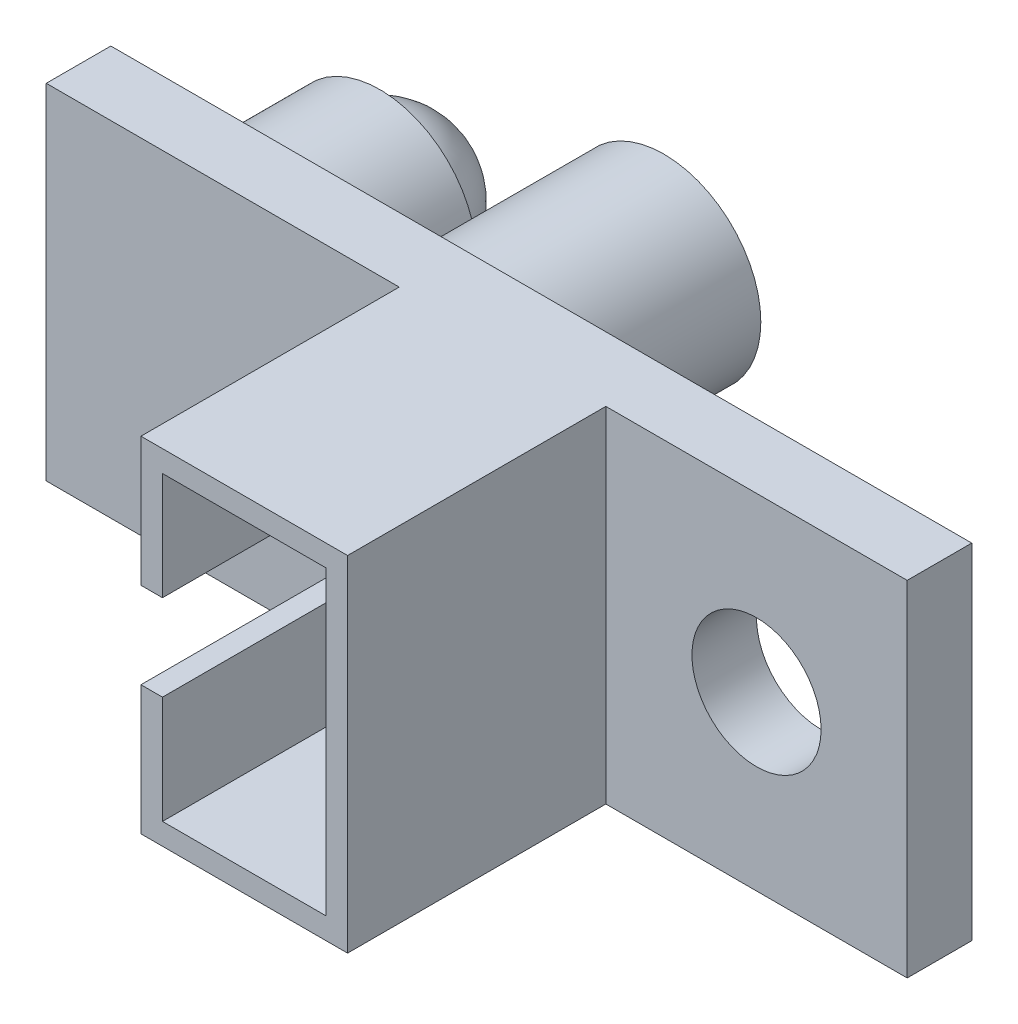
SolidWorks part; units mm, degrees
ref_plane "前视基准面" through (0, 0, 0) normal (0, 0, 1) x (1, 0, 0)
ref_plane "上视基准面" through (0, 0, 0) normal (0, 1, 0) x (1, 0, 0)
ref_plane "右视基准面" through (0, 0, 0) normal (1, 0, 0) x (0, 0, -1)
sketch "草图1" plane through (0, 0, 0) normal (0, 0, 1) x (1, 0, 0)
  line L1 (-10, 4) -> (10, 4)
  line L2 (-10, 4) -> (-10, -4)
  line L3 (-10, -4) -> (10, -4)
  line L4 (10, 4) -> (10, -4)
  line L5 (-10, 4) -> (10, -4) construction
  line L6 (-10, -4) -> (10, 4) construction
  point P0 (0, 0)
  dimension "D1" = 8
  dimension "D2" = 20
extrude "凸台-拉伸1" add sketch "草图1" along normal blind 1.5
sketch "草图2" plane through (0, 0, 1.5) normal (0, 0, 1) x (1, 0, 0)
  line L0 (10, -4) -> (10, 4) construction
  circle A0 centre (6.5, 0) radius 1.5
  dimension "D1" = 3
  dimension "D2" = 3.5
extrude "切除-拉伸1" cut sketch "草图2" against normal blind 1.5
sketch "草图3" plane through (0, 0, 1.5) normal (0, 0, 1) x (1, 0, 0)
  line L0 (10, 4) -> (-10, 4) construction
  line L1 (-1.8, 4) -> (3, 4)
  line L2 (-1.8, 4) -> (-1.8, -4)
  line L3 (-1.8, -4) -> (3, -4)
  line L4 (3, 4) -> (3, -4)
  line L5 (-10, -4) -> (10, -4) construction
  line L6 (10, -4) -> (10, 4) construction
  line L7 (-1.3, 3.5) -> (2.5, 3.5)
  line L8 (2.5, 3.5) -> (2.5, -3.5)
  line L9 (-1.3, -3.5) -> (2.5, -3.5)
  line L10 (-1.3, 3.5) -> (-1.3, -3.5)
  dimension "D1" = 7
  dimension "D2" = 4.8
  dimension "D3" = 0.5
extrude "凸台-拉伸2" add sketch "草图3" along normal blind 6
sketch "草图4" plane through (-1.8, 0, 0) normal (-1, 0, 0) x (0, 0, 1)
  line L0 (7.5, 4) -> (7.5, -4) construction
  line L1 (3, 1) -> (7.5, 1)
  line L2 (3, 1) -> (3, -1)
  line L3 (3, -1) -> (7.5, -1)
  line L4 (7.5, 1) -> (7.5, -1)
  line L5 (3, 1) -> (7.5, -1) construction
  line L6 (3, -1) -> (7.5, 1) construction
  point P0 (5.25, 0)
  dimension "D1" = 4.5
  dimension "D2" = 2
extrude "切除-拉伸4" cut sketch "草图4" against normal blind 1
sketch "草图5" plane through (0, 0, 0) normal (0, 0, -1) x (-1, 0, 0)
  line L0 (10, 4) -> (10, -4) construction
  line L1 (5.5, 0) -> (5.5, 1.5149) construction
  circle A0 centre (7.75, 0) radius 2.25
  circle A1 centre (7.75, 0) radius 1.75
  dimension "D1" = 4.5
  dimension "D2" = 0.5
extrude "凸台-拉伸3" add sketch "草图5" along normal blind 4
sketch "草图6" plane through (0, 0, -4) normal (0, 0, -1) x (-1, 0, 0)
  line L0 (7.75, 1.75) -> (7.75, -1.75)
  circle A0 centre (7.75, 0) radius 1.75 construction
  arc A1 (7.75, -1.75) -> (7.75, 1.75) centre (7.75, 0) ccw
revolve "旋转1" add sketch "草图6" angle 360 about L0
sketch "草图8" plane through (0, 0, 0) normal (0, 0, -1) x (-1, 0, 0)
  circle A0 centre (3.15, 0) radius 2.25
  circle A2 centre (3.15, 0) radius 1.75
  circle A3 centre (7.75, 0) radius 2.25 construction
  dimension "D1" = 4.5
  dimension "D2" = 3.5
  dimension "D3" = 4.6
extrude "凸台-拉伸13" add sketch "草图8" along normal blind 4
sketch "草图9" plane through (0, 0, -4) normal (0, 0, -1) x (-1, 0, 0)
  line L0 (3.15, 1.75) -> (3.15, -1.75)
  circle A0 centre (3.15, 0) radius 1.75 construction
  arc A1 (3.15, -1.75) -> (3.15, 1.75) centre (3.15, 0) ccw
revolve "旋转2" add sketch "草图9" angle 360 about L0
sketch "草图10" plane through (0, 0, -4) normal (0, 0, -1) x (-1, 0, 0)
  circle A0 centre (3.15, 0) radius 1.75
  circle A1 centre (3.15, 0) radius 2.25
  circle A2 centre (3.15, 0) radius 2.25
  dimension "D1" = 0
  dimension "D2" = 0.5
extrude "凸台-拉伸14" add sketch "草图10" along normal blind 2
sketch "草图11" plane through (0, 0, 0) normal (0, 0, -1) x (-1, 0, 0)
  circle A0 centre (3.15, 0) radius 1.75 construction
  circle A1 centre (3.15, 0) radius 1.75
extrude "凸台-拉伸15" add sketch "草图11" along normal blind 4
